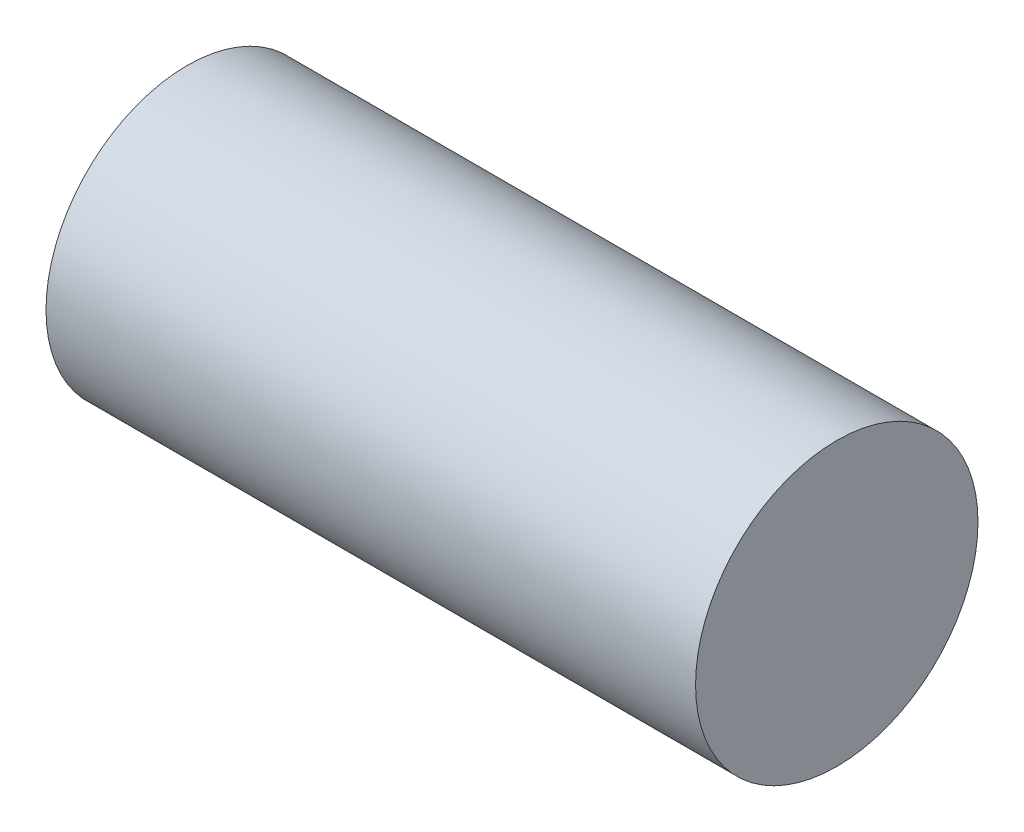
SolidWorks part; units mm, degrees
ref_plane "Front Plane" through (0, 0, 0) normal (0, 0, 1) x (1, 0, 0)
ref_plane "Top Plane" through (0, 0, 0) normal (0, 1, 0) x (1, 0, 0)
ref_plane "Right Plane" through (0, 0, 0) normal (1, 0, 0) x (0, 0, -1)
sketch "Sketch1" plane through (0, 0, 0) normal (1, 0, 0) x (0, 0, -1)
  circle A0 centre (0, 0) radius 2
  dimension "D1" = 4
extrude "Boss-Extrude1" add sketch "Sketch1" along normal blind 9.2
